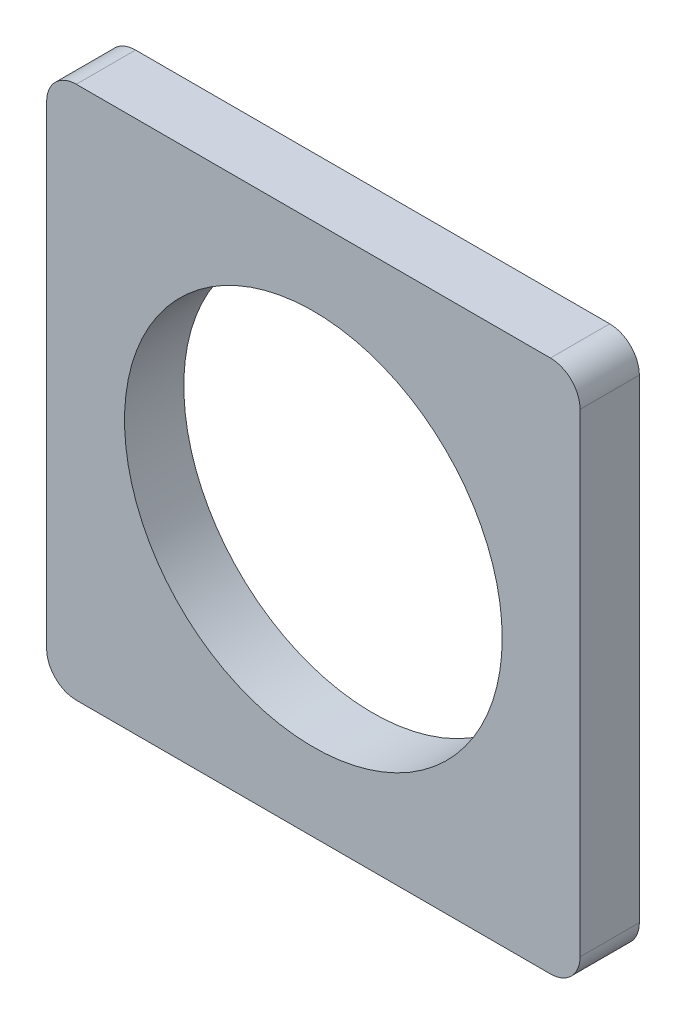
SolidWorks part; units mm, degrees
material "Acrylic (Medium-high impact)"
ref_plane "Front Plane" through (0, 0, 0) normal (0, 0, 1) x (1, 0, 0)
ref_plane "Top Plane" through (0, 0, 0) normal (0, 1, 0) x (1, 0, 0)
ref_plane "Right Plane" through (0, 0, 0) normal (1, 0, 0) x (0, 0, -1)
sketch "Sketch1" plane through (0, 0, 0) normal (0, 0, 1) x (1, 0, 0)
  line L1 (79.2825, -27.2927) -> (136.4325, -27.2927)
  line L2 (79.2825, -27.2927) -> (79.2825, 29.8573)
  line L3 (79.2825, 29.8573) -> (136.4325, 29.8573)
  line L4 (136.4325, -27.2927) -> (136.4325, 29.8573)
  line L5 (79.2825, -27.2927) -> (136.4325, 29.8573) construction
  line L6 (79.2825, 29.8573) -> (136.4325, -27.2927) construction
  circle A0 centre (107.8575, 1.2823) radius 20.2311 construction
  circle A1 centre (107.8575, 1.2823) radius 20.2311
  dimension "D1" = 28.575
  dimension "D2" = 28.575
extrude "Boss-Extrude1" add sketch "Sketch1" along normal blind 6.35
fillet "Fillet1" radius 3.175 4 edges at (79.2825, -27.2927, 3.175) (136.4325, -27.2927, 3.175) (79.2825, 29.8573, 3.175) (136.4325, 29.8573, 3.175)
